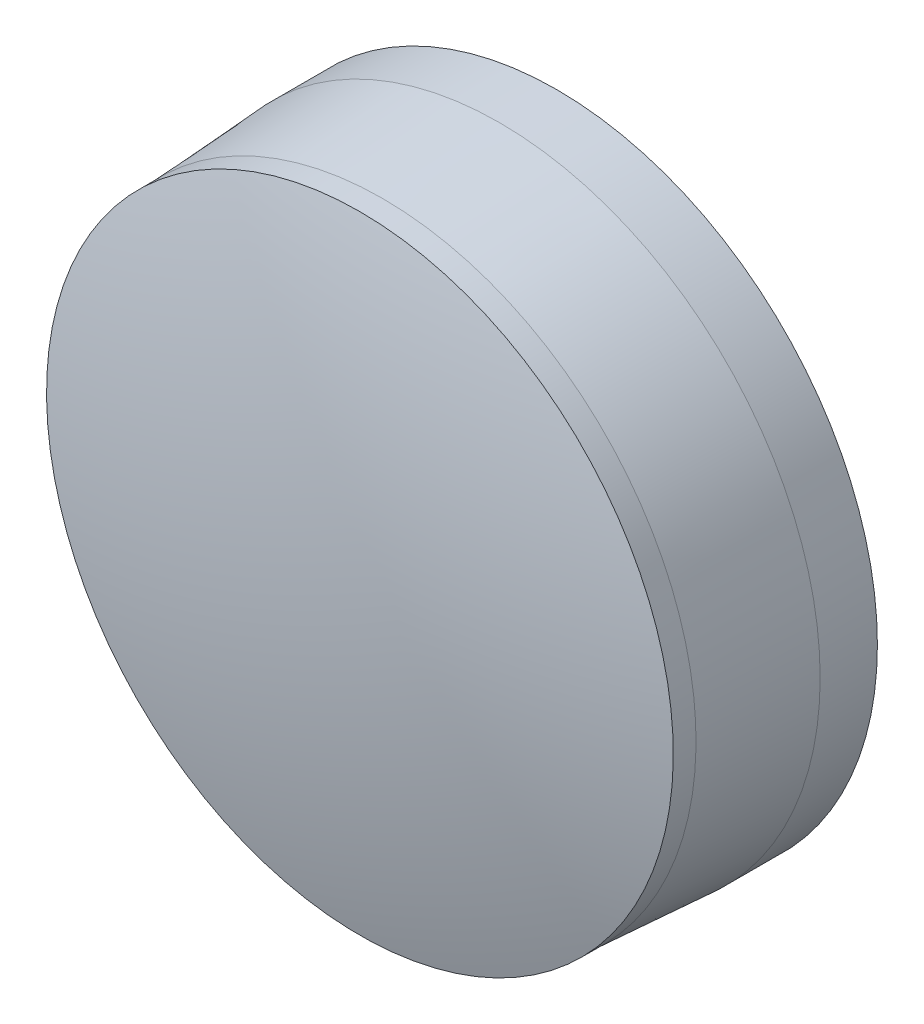
SolidWorks part; units mm, degrees
ref_plane "Front Plane" through (0, 0, 0) normal (0, 0, 1) x (1, 0, 0)
ref_plane "Top Plane" through (0, 0, 0) normal (0, 1, 0) x (1, 0, 0)
ref_plane "Right Plane" through (0, 0, 0) normal (1, 0, 0) x (0, 0, -1)
sketch "Sketch1" plane through (0, 0, 0) normal (1, 0, 0) x (0, 0, -1)
  line L0 (-4.5, 0) -> (0, 0)
  line L1 (-3.3851, 5.475) -> (-1.3414, 5.6)
  line L2 (-3.3851, 5.475) -> (-3.7825, 5.475)
  line L3 (-0.3414, 5.6) -> (-1.3414, 5.6)
  line L4 (11.2668, 0) -> (-5.8489, 0) construction
  line L5 (-3.8664, 5.15) -> (-0.2999, 5.25) construction
  arc A0 (-3.7825, 5.475) -> (-4.5, 0) centre (16.7481, 0) ccw
  arc A1 (0, 0) -> (-0.3414, 5.6) centre (-46.1017, 0) ccw
  dimension "D1" = 21.2481
  dimension "D3" = 4.5
  dimension "D9" = 46.1017
  dimension "D2" = 10.95
  dimension "D4" = 11.2
  dimension "D5" = 1
  dimension "D6" = 3.5
  dimension "D7" = 10.5
  dimension "D8" = 10.3
revolve "Revolve1" add sketch "Sketch1" angle 360 about L4
ref_plane "Plane1" through (0, 0, 0.3599) normal (0, 0, 1) x (1, 0, 0)
sketch "Sketch3" plane through (0, 0, 0) normal (0, 0, 1) x (1, 0, 0)
  point P0 (0, 0)
ref_point "Point1"
sketch "Sketch2" plane through (0, 0, 0.3599) normal (0, 0, 1) x (1, 0, 0)
  line L0 (0, 0) -> (8.85, 0) construction
  line L1 (8.85, -1.25) -> (8.85, 1.25)
  line L2 (8.85, 1.25) -> (5.0077, 1.9275)
  line L3 (5.0077, 1.9275) -> (5.0077, -1.9275)
  line L4 (8.85, -1.25) -> (5.0077, -1.9275)
  line L5 (5.1327, 1.9055) -> (5.1327, -1.9055) construction
  circle A1 centre (0, 0) radius 5.6 construction
  circle A2 centre (0, 0) radius 5.475 construction
  point P12 (5.0077, 0)
  dimension "D1" = 3.25
  dimension "D2" = 20
  dimension "D3" = 2.5
  dimension "D4" = 0.25
extrude "Gate" [suppressed] add sketch "Sketch2" along normal blind 2.5 draft 3
fillet "Fillet1" [suppressed] radius 0.7874
